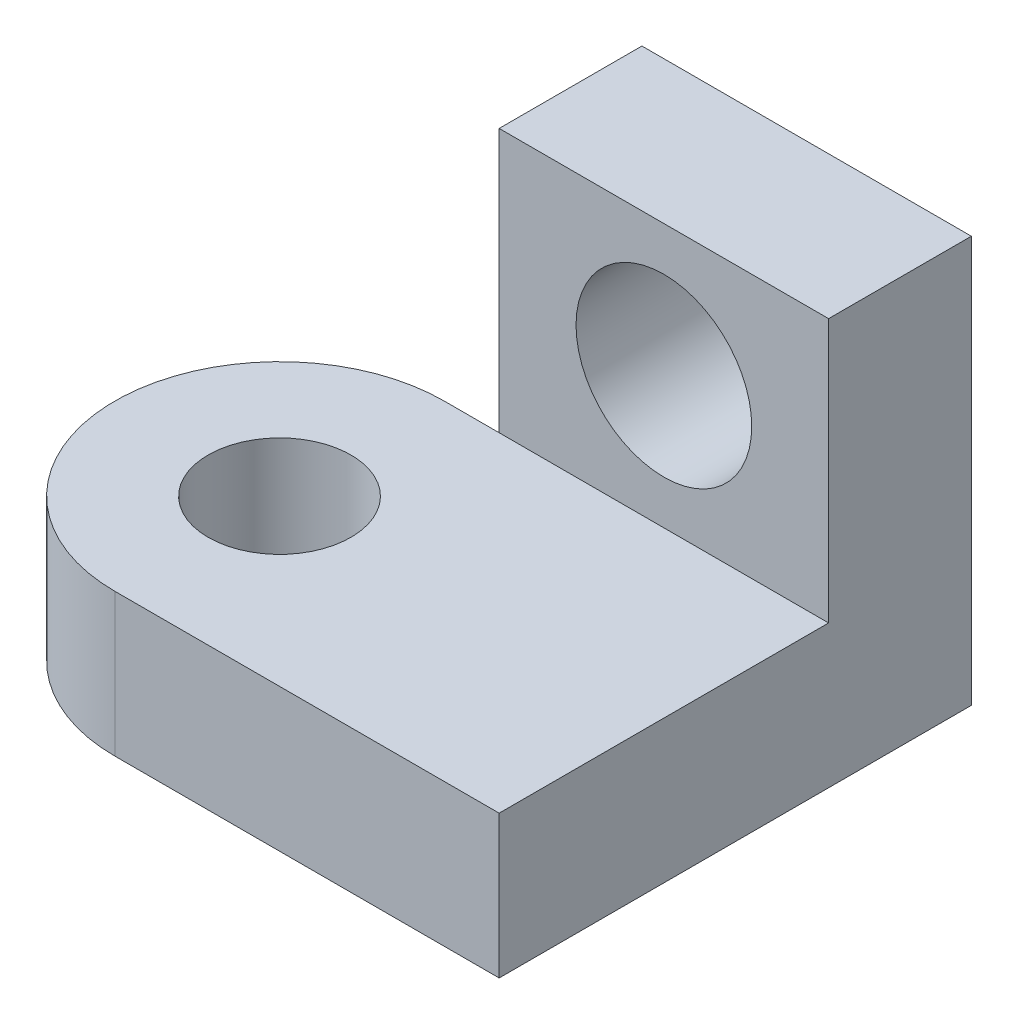
SolidWorks part; units mm, degrees
ref_plane "Plano frontal" through (0, 0, 0) normal (0, 0, 1) x (1, 0, 0)
ref_plane "Plano superior" through (0, 0, 0) normal (0, 1, 0) x (1, 0, 0)
ref_plane "Plano direito" through (0, 0, 0) normal (1, 0, 0) x (0, 0, -1)
sketch "Esboço1" plane through (0, 0, 0) normal (0, 0, 1) x (1, 0, 0)
  line L0 (0, 0) -> (0, 24)
  line L1 (0, 24) -> (30, 24)
  line L2 (30, 24) -> (30, 0)
  line L3 (30, 0) -> (0, 0)
  line L8 (15, 24) -> (15, 0) construction
  line L9 (0, 12) -> (30, 12) construction
  circle A0 centre (15, 12) radius 8
  dimension "D5" = 16
  dimension "D1" = 24
  dimension "D2" = 30
  dimension "D4" = 12
extrude "Ressalto-extrusão3" add sketch "Esboço1" along normal blind 13
sketch "Esboço5" plane through (0, 0, 0) normal (-1, 0, 0) x (0, 0, 1)
  line L0 (13, 0) -> (13, -13)
  line L1 (13, -13) -> (0, -13)
  line L2 (0, -13) -> (0, 0)
  line L4 (13, 24) -> (0, 24) construction
  line L5 (13, 0) -> (0, 0)
  dimension "D1" = 37
extrude "Ressalto-extrusão4" add sketch "Esboço5" against normal blind 30 contours L0 L1 L2 L5
sketch "Esboço7" plane through (0, -13, 0) normal (0, -1, 0) x (1, 0, 0)
  line L0 (-5, 13) -> (30, 13)
  line L1 (30, 13) -> (30, 43)
  line L3 (30, 0) -> (0, 0) construction
  line L4 (-5, 43) -> (30, 43)
  line L5 (-14.7977, 28) -> (4.7977, 28) construction
  line L6 (-5, 37.7977) -> (-5, 18.2023) construction
  arc A3 (-5, 43) -> (-5, 13) centre (-5, 28) ccw
  circle A4 centre (-5, 28) radius 6.5
  dimension "D2" = 15
  dimension "D1" = 13
  dimension "D3" = 35
  dimension "D4" = 43
extrude "Ressalto-extrusão6" add sketch "Esboço7" against normal blind 13 contours L4 L1 L0 A3
sketch "Esboço8" plane through (0, 0, 0) normal (0, 1, 0) x (1, 0, 0)
  circle A0 centre (-5, -28) radius 6.5
  point P3 (0, 0)
  point P5 (0, 0)
  point P6 (0, 0)
  dimension "D1" = 13
  dimension "D2" = 35
extrude "Corte-extrusão1" cut sketch "Esboço8" against normal blind 13
